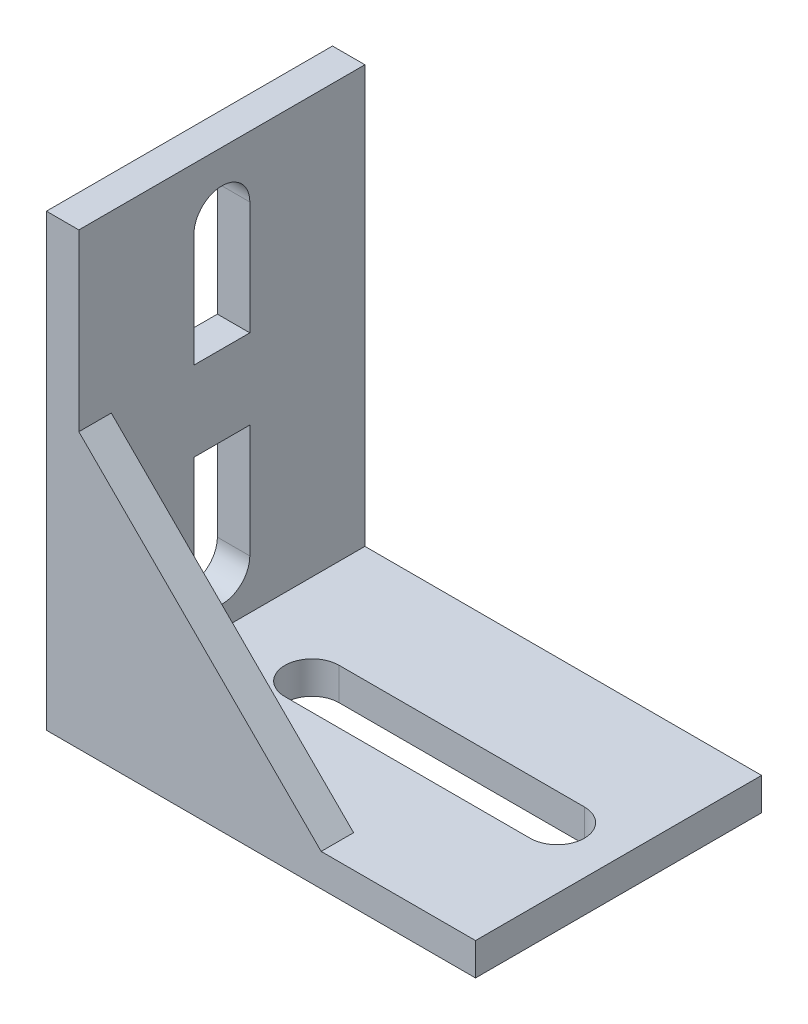
SolidWorks part; units mm, degrees
material "Fundición maleable"
ref_plane "Alzado" through (0, 0, 0) normal (0, 0, 1) x (1, 0, 0)
ref_plane "Planta" through (0, 0, 0) normal (0, 1, 0) x (1, 0, 0)
ref_plane "Vista lateral" through (0, 0, 0) normal (1, 0, 0) x (0, 0, -1)
sketch "Croquis1" plane through (0, 0, 0) normal (1, 0, 0) x (0, 0, -1)
  line L0 (-45.4025, -30) -> (55.245, -30) construction
  line L1 (0, 65) -> (0, -10) construction
  line L2 (-35, 80) -> (35, 80) construction
  line L3 (-35, 80) -> (-35, -80) construction
  line L4 (-35, -80) -> (35, -80) construction
  line L5 (35, 80) -> (35, -80) construction
  line L6 (-35, 80) -> (35, -80) construction
  line L7 (-35, -80) -> (35, 80) construction
  line L8 (-35, 80) -> (35, 80)
  line L9 (-35, 80) -> (-35, -30)
  line L10 (-35, -30) -> (35, -30)
  line L11 (35, 80) -> (35, -30)
  line L12 (6.8348, 65) -> (6.8348, -10)
  line L13 (-6.8348, 65) -> (-6.8348, -10)
  line L15 (-6.8348, 17.7337) -> (6.8348, 17.7337)
  line L16 (-6.8348, 17.7337) -> (-6.8348, 37.2663)
  line L17 (-6.8348, 37.2663) -> (6.8348, 37.2663)
  line L18 (6.8348, 17.7337) -> (6.8348, 37.2663)
  line L19 (-6.8348, 17.7337) -> (6.8348, 37.2663) construction
  line L20 (-6.8348, 37.2663) -> (6.8348, 17.7337) construction
  circle A0 centre (0, 0) radius 6.35
  circle A1 centre (0, 65) radius 6.35
  arc A2 (6.8348, 65) -> (-6.8348, 65) centre (0, 65) ccw
  arc A3 (-6.8348, -10) -> (6.8348, -10) centre (0, -10) ccw
  point P13 (0, 27.5)
  point P19 (0, 27.5)
  dimension "D1" = 12.7
  dimension "D2" = 12.7
  dimension "D3" = 65
  dimension "D4" = 30
  dimension "D5" = 70
  dimension "D6" = 110
  dimension "D7" = 75
extrude "Saliente-Extruir1" add sketch "Croquis1" along normal blind 7.9375
sketch "Croquis2" plane through (0, -30, 0) normal (0, -1, 0) x (1, 0, 0)
  line L0 (0, 0) -> (105, 0) construction
  line L1 (0, 35) -> (105, 35)
  line L2 (0, 35) -> (0, -35)
  line L3 (0, -35) -> (105, -35)
  line L4 (105, 35) -> (105, -35)
  line L5 (30, 0) -> (90, 0) construction
  line L6 (30, 6.6403) -> (90, 6.6403)
  line L7 (30, -6.6403) -> (90, -6.6403)
  circle A0 centre (30, 0) radius 6.35
  circle A1 centre (90, 0) radius 6.35
  arc A2 (30, 6.6403) -> (30, -6.6403) centre (30, 0) ccw
  arc A3 (90, -6.6403) -> (90, 6.6403) centre (90, 0) ccw
  point P11 (60, 0)
  line M12 (7.9375, -35) -> (7.9375, 35)
  dimension "D1" = 12.7
  dimension "D2" = 12.7
  dimension "D3" = 30
  dimension "D4" = 60
  dimension "D5" = 105
  dimension "D6" = 70
extrude "Saliente-Extruir2" add sketch "Croquis2" against normal blind 7.9375 contours L4 L1 L3 A3 L7 A2 L6 M12
sketch "Croquis3" plane through (0, 0, 35) normal (0, 0, -1) x (-1, 0, 0)
  line L0 (0, 45.1664) -> (-75.1664, -30)
  line L1 (0, 80) -> (0, -30) construction
  line L2 (-105, -30) -> (0, -30) construction
  line L3 (-75.1664, -30) -> (0, -30)
  line L4 (0, -30) -> (0, 45.1664)
  dimension "D1" = 45
extrude "Saliente-Extruir3" add sketch "Croquis3" along normal blind 7.9375
